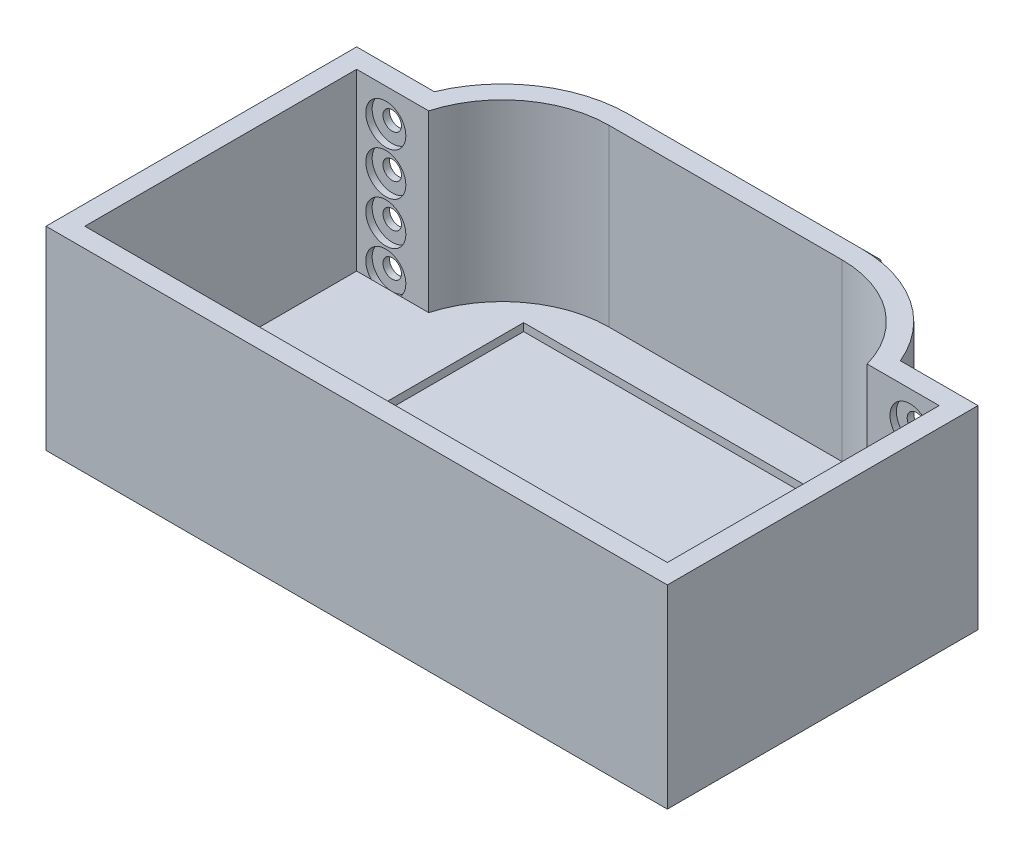
SolidWorks part; units mm, degrees
ref_plane "Front Plane" through (0, 0, 0) normal (0, 0, 1) x (1, 0, 0)
ref_plane "Top Plane" through (0, 0, 0) normal (0, 1, 0) x (1, 0, 0)
ref_plane "Right Plane" through (0, 0, 0) normal (1, 0, 0) x (0, 0, -1)
sketch "Sketch1" plane through (0, 0, 0) normal (0, 1, 0) x (1, 0, 0)
  line L1 (0, 0) -> (160, 0)
  line L2 (0, 0) -> (0, 80)
  line L5 (80, -79.4698) -> (80, 299.4698) construction
  line L6 (0, 80) -> (20, 80)
  line L7 (160, 80) -> (140, 80)
  line L8 (160, 0) -> (160, 80)
  line L10 (95, 120) -> (65, 120)
  line L12 (95, 120) -> (100, 100)
  line L13 (65, 120) -> (60, 100)
  line L16 (110, 100) -> (100, 100)
  line L17 (50, 100) -> (60, 100)
  arc A0 (20, 80) -> (50, 100) centre (50, 67.5) cw
  arc A1 (140, 80) -> (110, 100) centre (110, 67.5) ccw
  point P1 (80, 100)
  point P3 (0, 0)
  point P15 (80, 0)
  point P17 (0, 0)
  point P19 (80, 120)
  point P20 (0, 0)
  point P35 (80, 100)
  dimension "D6" = 40
  dimension "D7" = 10
  dimension "D1" = 80
  dimension "D2" = 80
  dimension "D3" = 30
  dimension "D4" = 20
  dimension "D5" = 30
  dimension "D8" = 20
  dimension "D9" = 20
extrude "Boss-Extrude1" add sketch "Sketch1" along normal blind 50
shell "Shell1" thickness 5
sketch "Sketch2" plane through (0, 5, 0) normal (0, 1, 0) x (1, 0, 0)
  line L0 (80, 5) -> (80, 95) construction
  line L1 (38, 85) -> (122, 85)
  line L2 (38, 85) -> (38, 20)
  line L3 (38, 20) -> (122, 20)
  line L4 (122, 85) -> (122, 20)
  line L5 (5, 5) -> (155, 5) construction
  dimension "D1" = 84
  dimension "D2" = 65
  dimension "D3" = 42
  dimension "D4" = 15
extrude "Cut-Extrude1" cut sketch "Sketch2" against normal blind 2
sketch "Sketch3" plane through (0, 5, 0) normal (0, 1, 0) x (1, 0, 0)
  line L0 (65, 120) -> (60, 100) construction
  line L1 (95, 120) -> (65, 120) construction
  line L2 (95, 120) -> (100, 100) construction
  line L3 (65, 120) -> (60, 100)
  line L4 (95, 120) -> (65, 120)
  line L5 (95, 120) -> (100, 100)
  line L6 (100, 100) -> (100, 95)
  line L7 (100, 95) -> (60, 95)
  line L8 (60, 95) -> (60, 100)
  line L9 (110, 95) -> (96.0961, 95) construction
extrude "Boss-Extrude2" add sketch "Sketch3" along normal up to surface (45 mm away) up to face at (80, 50, -80.7569)
chamfer "Chamfer1" distance 20 angle 45 1 edges at (80, 50, -120)
hole_wizard "Hole1" positions "3DSketch2" profile "Sketch6" legacy end condition through all
sketch3d "3DSketch2"
  line L2 (80, 30, -120) -> (80, 30, -100) construction
  line L3 (65, 30, -120) -> (95, 30, -120) construction
  line L7 (100, 50, -100) -> (60, 50, -100) construction
  line L8 (65, 30, -120) -> (65, 30, -100) construction
  line L10 (65, 30, -110) -> (80, 30, -110) construction
  line L11 (95, 30, -120) -> (95, 30, -100) construction
  line L14 (80, 30, -110) -> (95, 30, -110) construction
  point P0 (72.5, 50, -110)
  point P29 (80, 50, -100)
  point P43 (72.5, 30, -110)
  point P44 (87.5, 50, -110)
  point P57 (0, 0, 0)
  point P58 (0, 0, 0)
  point P59 (87.5, 30, -110)
sketch "Sketch6" plane through (72.5, 50, -110) normal (1, 0, 0) x (0, 0, 1)
  line L0 (0, 0) -> (0, 50)
  line L1 (0, 50) -> (2.125, 50)
  line L2 (2.125, 50) -> (2.125, 40)
  line L3 (2.125, 40) -> (5.125, 40)
  line L4 (5.125, 40) -> (5.125, 0)
  line L5 (5.125, 0) -> (0, 0)
  line L6 (0, 110) -> (0, -10) construction
  dimension "Diameter" = 4.25
  dimension "Depth" = 50
  dimension "C-Bore Diameter" = 10.25
  dimension "C-Bore Depth" = 40
ref_plane "Plane1" through (0, 0, -77.5) normal (0, 0, 1) x (1, 0, 0)
sketch "Sketch9" plane through (0, 0, -80) normal (0, 0, -1) x (-1, 0, 0)
  line L0 (-147.5, 50) -> (-147.5, 46.6594) construction
  line L1 (-155, 50) -> (-140, 50) construction
  line L5 (-147.5, 0) -> (-147.5, 3.3406) construction
  line L7 (-160, 50) -> (-140, 50) construction
  line L8 (-160, 0) -> (-140, 0) construction
  circle A0 centre (-147.5, 41.5) radius 5.1594
  circle A1 centre (-147.5, 30.5) radius 5.1594
  circle A2 centre (-147.5, 19.5) radius 5.1594
  circle A3 centre (-147.5, 8.5) radius 5.1594
  point P13 (0, 0)
  point P14 (0, 0)
  point P16 (-147.5, 50)
  point P19 (0, 0)
  dimension "D1" = 4
  dimension "D3" = 10.3187
  dimension "D2" = 11
extrude "Cut-Extrude2" cut sketch "Sketch9" against normal blind 1.6491
mirror "Mirror1" about plane through (0, 0, -77.5) normal (0, 0, 1) of "Cut-Extrude2"
sketch "Sketch11" plane through (0, 0, -80) normal (0, 0, -1) x (-1, 0, 0)
  circle A9 centre (-147.5, 41.5) radius 2.3813
  circle A10 centre (-147.5, 30.5) radius 2.3813
  circle A11 centre (-147.5, 19.5) radius 2.3813
  circle A12 centre (-147.5, 8.5) radius 2.3813
  dimension "D1" = 4.7625
extrude "Cut-Extrude3" cut sketch "Sketch11" against normal up to surface (5 mm away) up to face at (142.3406, 41.5, -75)
ref_plane "Plane2" through (80, 0, 0) normal (1, 0, 0) x (0, 0, -1)
mirror "Mirror2" about plane through (80, 0, 0) normal (1, 0, 0) of "Cut-Extrude2", "Mirror1", "Cut-Extrude3"
